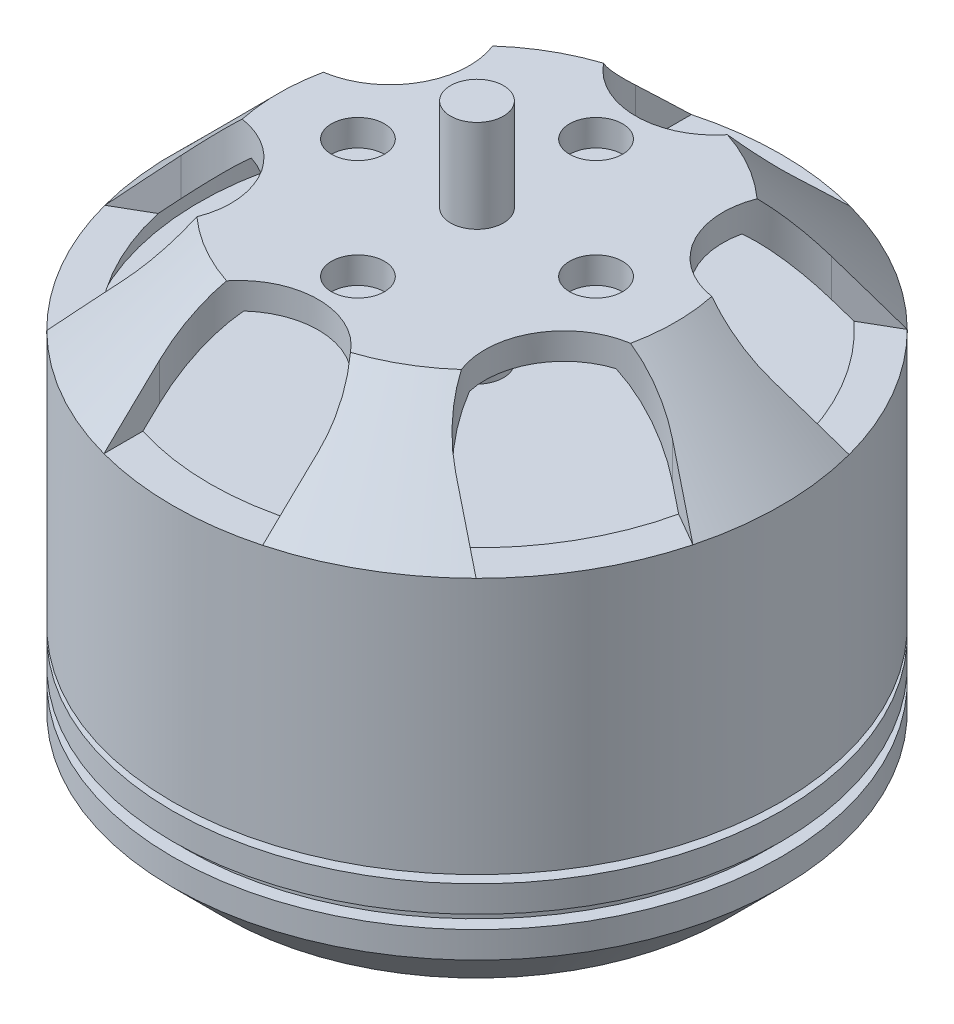
SolidWorks part; units mm, degrees
ref_plane "Front Plane" through (0, 0, 0) normal (0, 0, 1) x (1, 0, 0)
ref_plane "Top Plane" through (0, 0, 0) normal (0, 1, 0) x (1, 0, 0)
ref_plane "Right Plane" through (0, 0, 0) normal (1, 0, 0) x (0, 0, -1)
sketch "Sketch1" plane through (0, 0, 0) normal (0, 0, 1) x (1, 0, 0)
  line L0 (0, 21.1538) -> (0, 0)
  line L1 (1, -0.8462) -> (9.5, -0.8462)
  line L2 (9.5, -0.8462) -> (11.5, 1.1538)
  line L3 (11.5, 1.1538) -> (11.5, 2.1538)
  line L4 (11.5, 13.6538) -> (7.5, 17.6538)
  line L5 (7.5, 17.6538) -> (1, 17.6538)
  line L6 (1, 17.6538) -> (1, 21.1538)
  line L7 (1, 21.1538) -> (0, 21.1538)
  line L8 (0, 0) -> (0, -2.6462)
  line L9 (0, -2.6462) -> (1, -2.6462)
  line L10 (1, -2.6462) -> (1, -0.8462)
  line L11 (2, 16.6538) -> (7.0858, 16.6538)
  line L12 (7.0858, 16.6538) -> (10.5, 13.2396)
  line L13 (10.5, 13.2396) -> (10.5, 12.5869)
  line L14 (10.5, 12.5869) -> (1, 12.5869)
  line L15 (1, 12.5869) -> (1, 15.6538)
  line L16 (1, 15.6538) -> (2, 15.6538)
  line L17 (2, 15.6538) -> (2, 16.6538)
  line L18 (11.5, 2.1538) -> (11, 2.1538)
  line L19 (11, 2.1538) -> (11, 2.6538)
  line L20 (11, 2.6538) -> (11.5, 2.6538)
  line L21 (11.5, 3.6538) -> (9.5, 3.6538)
  line L22 (9.5, 3.6538) -> (9.5, 3.9538)
  line L23 (9.5, 3.9538) -> (11.5, 3.9538)
  line L24 (11.5, 3.9538) -> (11.5, 13.6538)
  line L25 (11.5, 2.6538) -> (11.5, 3.6538)
  point P8 (0.5, -2.6462)
  dimension "D1" = 23.8
  dimension "D2" = 1.8
  dimension "D3" = 1
  dimension "D4" = 2
  dimension "D5" = 11.5
  dimension "D6" = 1
  dimension "D7" = 1
  dimension "D8" = 3.5
  dimension "D9" = 1
  dimension "D10" = 1
  dimension "D11" = 1
  dimension "D12" = 1
  dimension "D13" = 1
  dimension "D14" = 4
  dimension "D15" = 45
  dimension "D16" = 0.5
  dimension "D17" = 0.5
  dimension "D18" = 1
  dimension "D19" = 2
  dimension "D20" = 0.3
  dimension "D21" = 1
revolve "Revolve1" add sketch "Sketch1" angle 360 about L0
sketch "Sketch2" plane through (0, 17.6538, 0) normal (0, 1, 0) x (1, 0, 0)
  line L0 (0, 0) -> (0, 9) construction
  line L1 (-3, 9) -> (-3, 16.489)
  line L2 (-3, 16.489) -> (3, 16.489)
  line L3 (3, 16.489) -> (3, 9)
  line L4 (15.7799, 5.6464) -> (9.2942, 1.9019)
  line L5 (12.7799, 10.8426) -> (15.7799, 5.6464)
  line L6 (6.2942, 7.0981) -> (12.7799, 10.8426)
  line L7 (12.7799, -10.8426) -> (6.2942, -7.0981)
  line L8 (15.7799, -5.6464) -> (12.7799, -10.8426)
  line L9 (9.2942, -1.9019) -> (15.7799, -5.6464)
  line L10 (-3, -16.489) -> (-3, -9)
  line L11 (3, -16.489) -> (-3, -16.489)
  line L12 (3, -9) -> (3, -16.489)
  line L13 (-15.7799, -5.6464) -> (-9.2942, -1.9019)
  line L14 (-12.7799, -10.8426) -> (-15.7799, -5.6464)
  line L15 (-6.2942, -7.0981) -> (-12.7799, -10.8426)
  line L16 (-12.7799, 10.8426) -> (-6.2942, 7.0981)
  line L17 (-15.7799, 5.6464) -> (-12.7799, 10.8426)
  line L18 (-9.2942, 1.9019) -> (-15.7799, 5.6464)
  circle A0 centre (0, 0) radius 4.5 construction
  circle A1 centre (0, 0) radius 8.6097 construction
  circle A2 centre (0, -4.5) radius 1
  circle A3 centre (-4.5, 0) radius 1
  circle A4 centre (0, 4.5) radius 1
  circle A5 centre (4.5, 0) radius 1
  arc A6 (-3, 9) -> (3, 9) centre (0, 9) ccw
  arc A7 (6.2942, 7.0981) -> (9.2942, 1.9019) centre (7.7942, 4.5) ccw
  arc A8 (9.2942, -1.9019) -> (6.2942, -7.0981) centre (7.7942, -4.5) ccw
  arc A9 (3, -9) -> (-3, -9) centre (0, -9) ccw
  arc A10 (-6.2942, -7.0981) -> (-9.2942, -1.9019) centre (-7.7942, -4.5) ccw
  arc A11 (-9.2942, 1.9019) -> (-6.2942, 7.0981) centre (-7.7942, 4.5) ccw
  dimension "D1" = 9
  dimension "D3" = 2
  dimension "D5" = 6
  dimension "D2" = 9
  dimension "D4" = 4
  dimension "D6" = 6
extrude "Cut-Extrude1" cut sketch "Sketch2" against normal blind 4
sketch "Sketch3" plane through (0, -0.8462, 0) normal (0, -1, 0) x (1, 0, 0)
  circle A0 centre (0, 0) radius 6 construction
  circle A1 centre (0, 0) radius 8 construction
  circle A2 centre (0, 6) radius 1
  circle A3 centre (0, -6) radius 1
  circle A4 centre (-8, 0) radius 1
  circle A5 centre (8, 0) radius 1
  dimension "D1" = 12
  dimension "D2" = 16
  dimension "D3" = 2
extrude "Cut-Extrude2" cut sketch "Sketch3" against normal blind 3
